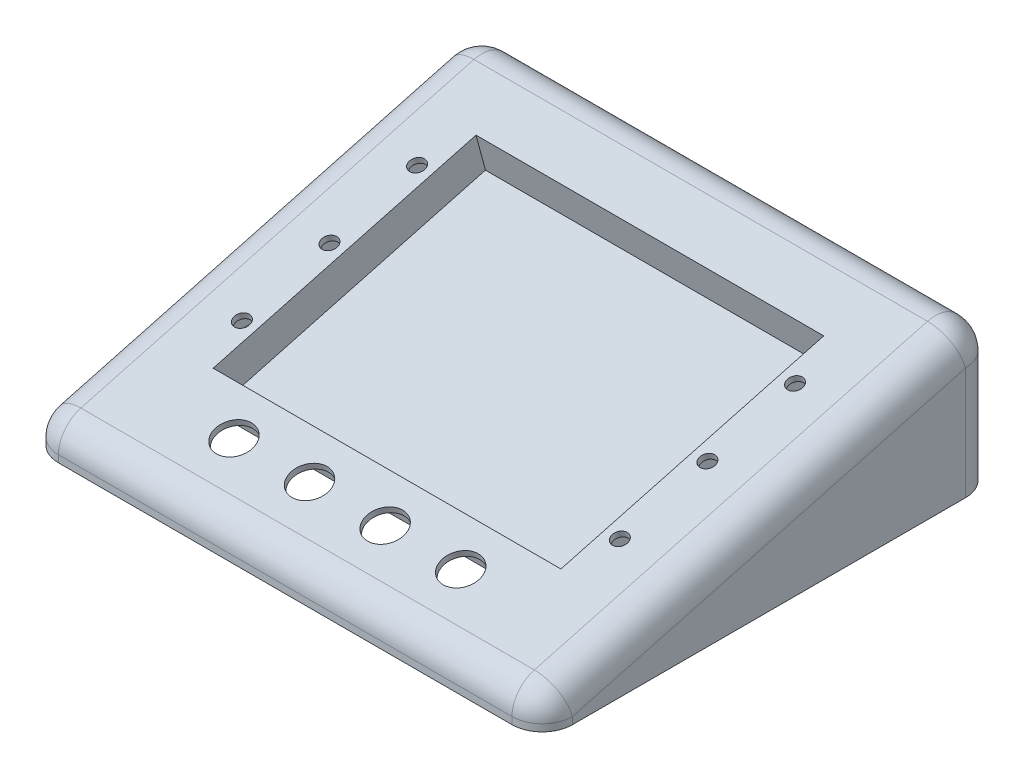
SolidWorks part; units mm, degrees
ref_plane "Front Plane" through (0, 0, 0) normal (0, 0, 1) x (1, 0, 0)
ref_plane "Top Plane" through (0, 0, 0) normal (0, 1, 0) x (1, 0, 0)
ref_plane "Right Plane" through (0, 0, 0) normal (1, 0, 0) x (0, 0, -1)
sketch "Sketch1" plane through (0, 0, 0) normal (0, 1, 0) x (1, 0, 0)
  line L1 (-85, 75) -> (85, 75)
  line L2 (-85, 75) -> (-85, -75)
  line L3 (-85, -75) -> (85, -75)
  line L4 (85, 75) -> (85, -75)
  line L5 (-85, 75) -> (85, -75) construction
  line L6 (-85, -75) -> (85, 75) construction
  point P0 (0, 0)
  dimension "D1" = 150
  dimension "D2" = 170
extrude "Boss-Extrude1" add sketch "Sketch1" along normal blind 10
sketch "Sketch2" plane through (-85, 0, 0) normal (-1, 0, 0) x (0, 0, 1)
  line L0 (-75, 10) -> (-75, 50.1924)
  line L1 (-75, 50.1924) -> (75, 10)
  line L2 (75, 10) -> (75, 0) construction
  line L3 (-75, 10) -> (75, 10) construction
  line L4 (75, 10) -> (-75, 10)
  dimension "D1" = 15
extrude "Boss-Extrude2" add sketch "Sketch2" against normal up to surface (170 mm away) up to face at (85, 5, 0)
fillet "Fillet1" radius 10 8 edges at (0, 10, 75) (85, 30.0962, 0) (-85, 30.0962, 0) (0, 50.1924, -75) (85, 5, 75) (85, 25.0962, -75) (-85, 25.0962, -75) (-85, 5, 75)
shell "Shell1" thickness 2
sketch "Sketch3" plane through (0, 28.0801, 7.524) normal (0, 0.9659, 0.2588) x (1, 0, 0)
  line L1 (-57.5, 55) -> (57.5, 55)
  line L2 (-57.5, 55) -> (-57.5, -35)
  line L3 (-57.5, -35) -> (57.5, -35)
  line L4 (57.5, 55) -> (57.5, -35)
  point P0 (0, -35)
  point P6 (0, 0)
  point P7 (57.5, 10)
  dimension "D1" = 115
  dimension "D2" = 90
  dimension "D3" = 10
extrude "Cut-Extrude1" cut sketch "Sketch3" against normal up to surface (2 mm away) up to face at (0, 27.4708, 2.0706)
sketch "Sketch4" plane through (0, 26.1483, 7.0064) normal (0, -0.9659, -0.2588) x (1, 0, 0)
  line L0 (-59.5, -57) -> (59.5, -57)
  line L1 (59.5, -57) -> (59.5, 37)
  line L2 (59.5, 37) -> (-59.5, 37)
  line L3 (-59.5, 37) -> (-59.5, -57)
  line L4 (-57.5, -55) -> (57.5, -55)
  line L5 (57.5, -55) -> (57.5, 35)
  line L6 (57.5, 35) -> (-57.5, 35)
  line L7 (-57.5, 35) -> (-57.5, -55)
  line L8 (-57.5, -55) -> (57.5, -55)
  line L9 (57.5, -55) -> (57.5, 35)
  line L10 (57.5, 35) -> (-57.5, 35)
  line L11 (-57.5, 35) -> (-57.5, -55)
  dimension "D1" = 0
  dimension "D2" = 2
extrude "Boss-Extrude3" add sketch "Sketch4" along normal blind 10
sketch "Sketch5" plane through (0, 16.489, 4.4182) normal (0, -0.9659, -0.2588) x (1, 0, 0)
  line L4 (-59.5, 37) -> (-59.5, -57)
  line L5 (-59.5, -57) -> (59.5, -57)
  line L6 (59.5, -57) -> (59.5, 37)
  line L7 (59.5, 37) -> (-59.5, 37)
  line L8 (-59.5, 37) -> (-59.5, -57)
  line L9 (-59.5, -57) -> (59.5, -57)
  line L10 (59.5, -57) -> (59.5, 37)
  line L11 (59.5, 37) -> (-59.5, 37)
  dimension "D1" = 0
extrude "Boss-Extrude4" add sketch "Sketch5" along normal blind 2
sketch "Sketch6" plane through (0, 28.0801, 7.524) normal (0, 0.9659, 0.2588) x (1, 0, 0)
  line L0 (-57.5, -35) -> (-57.5, 55) construction
  line L1 (-57.5, 55) -> (-57.5, -35) construction
  line L2 (0, -25.9381) -> (0, 25.9381) construction
  circle A0 centre (-62.5, 10) radius 2.5
  circle A1 centre (-62.5, 40) radius 2.5
  circle A2 centre (-62.5, -20) radius 2.5
  circle A3 centre (62.5, -20) radius 2.5
  circle A4 centre (62.5, 40) radius 2.5
  circle A5 centre (62.5, 10) radius 2.5
  point P6 (0, 0)
  point P9 (-57.5, 10)
  dimension "D4" = 5
  dimension "D1" = 5
  dimension "D2" = 30
  dimension "D3" = 30
extrude "Cut-Extrude2" cut sketch "Sketch6" against normal up to surface (2 mm away) up to face at (0, 27.4708, 2.0706)
sketch "Sketch7" plane through (0, 28.0801, 7.524) normal (0, 0.9659, 0.2588) x (1, 0, 0)
  line L5 (-37.5, -48.5915) -> (37.5, -48.5915) construction
  line L9 (-57.5, -35) -> (-57.5, -62.183) construction
  line L10 (-75, -62.183) -> (75, -62.183) construction
  circle A0 centre (-12.5, -48.5915) radius 6
  circle A1 centre (12.5, -48.5915) radius 6
  circle A2 centre (37.5, -48.5915) radius 6
  circle A3 centre (-37.5, -48.5915) radius 6
  point P9 (-57.5, -48.5915)
  point P10 (15.1197, -48.5915)
  point P12 (0, -48.5915)
  dimension "D1" = 12
  dimension "D2" = 25
  dimension "D3" = 75
  dimension "D4" = 12.5
extrude "Cut-Extrude3" cut sketch "Sketch7" against normal up to surface (2 mm away) up to face at (-62.5, 35.854, -29.2158)
